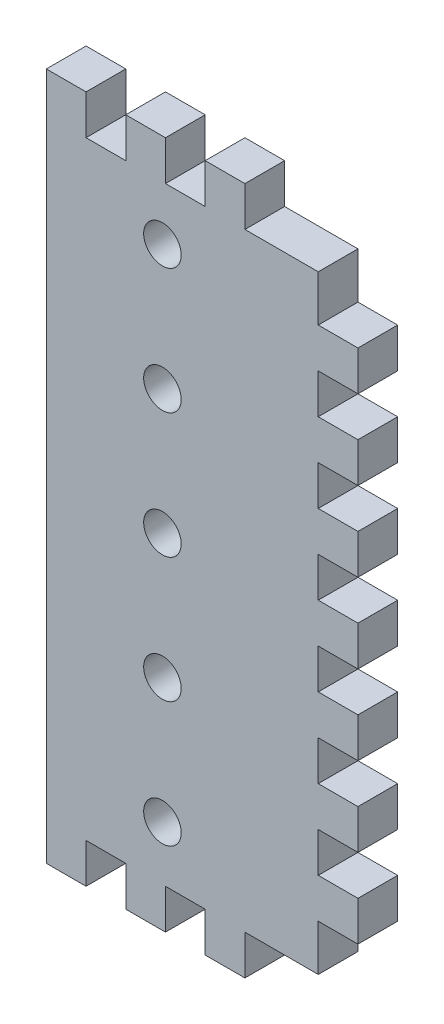
SolidWorks part; units mm, degrees
ref_plane "Front Plane" through (0, 0, 0) normal (0, 0, 1) x (1, 0, 0)
ref_plane "Top Plane" through (0, 0, 0) normal (0, 1, 0) x (1, 0, 0)
ref_plane "Right Plane" through (0, 0, 0) normal (1, 0, 0) x (0, 0, -1)
sketch "Sketch1" plane through (0, 0, 0) normal (0, 0, 1) x (1, 0, 0)
  line L1 (15.6312, -27.5) -> (-15.6312, -27.5)
  line L2 (15.6312, -27.5) -> (15.6312, 27.5)
  line L3 (15.6312, 27.5) -> (-15.6312, 27.5)
  line L4 (-15.6312, -27.5) -> (-15.6312, 27.5)
  line L5 (15.6312, -27.5) -> (-15.6312, 27.5) construction
  line L6 (15.6312, 27.5) -> (-15.6312, -27.5) construction
  point P0 (0, 0)
  dimension "D1" = 31.2625
  dimension "D2" = 55
extrude "Boss-Extrude1" add sketch "Sketch1" along normal blind 3.175
sketch "Sketch2" plane through (0, 0, 3.175) normal (0, 0, 1) x (1, 0, 0)
  line L0 (-15.6312, 27.5) -> (-15.6312, -27.5) construction
  circle A0 centre (0, 0) radius 1.5
  dimension "D1" = 3
extrude "Cut-Extrude1" cut sketch "Sketch2" against normal blind 10
pattern_linear "LPattern1" count 3 spacing 10 along (0, 1, 0) count 3 spacing 10 along (0, -1, 0) of "Cut-Extrude1"
sketch "Sketch3" plane through (0, 0, 3.175) normal (0, 0, 1) x (1, 0, 0)
  line L0 (15.6312, -27.5) -> (15.6312, 27.5) construction
  line L1 (12.4563, -1.5875) -> (18.8062, -1.5875)
  line L2 (12.4563, -1.5875) -> (12.4563, -4.7625)
  line L3 (12.4563, -4.7625) -> (18.8062, -4.7625)
  line L4 (18.8062, -1.5875) -> (18.8062, -4.7625)
  line L5 (12.4563, -1.5875) -> (18.8062, -4.7625) construction
  line L6 (12.4563, -4.7625) -> (18.8062, -1.5875) construction
  point P0 (15.6312, -3.175)
  dimension "D1" = 3.175
  dimension "D2" = 6.35
  dimension "D3" = 3.175
extrude "Cut-Extrude2" cut sketch "Sketch3" against normal blind 10
pattern_linear "LPattern2" count 5 spacing 6.35 along (0, 1, 0) count 5 spacing 6.35 along (0, -1, 0) of "Cut-Extrude2"
sketch "Sketch4" plane through (0, 0, 3.175) normal (0, 0, 1) x (1, 0, 0)
  line L1 (12.4563, 23.8125) -> (15.6312, 23.8125)
  line L2 (12.4563, 23.8125) -> (12.4563, 27.5)
  line L3 (12.4563, 27.5) -> (15.6312, 27.5)
  line L4 (15.6312, 23.8125) -> (15.6312, 27.5)
  line L5 (12.4563, -23.8125) -> (15.6312, -23.8125)
  line L6 (12.4563, -23.8125) -> (12.4563, -26.9875)
  line L7 (12.4563, -26.9875) -> (15.6312, -26.9875)
  line L8 (15.6312, -23.8125) -> (15.6312, -26.9875)
extrude "Cut-Extrude3" cut sketch "Sketch4" against normal blind 10
sketch "Sketch5" plane through (0, 0, 3.175) normal (0, 0, 1) x (1, 0, 0)
  line L0 (-15.6312, -27.5) -> (12.4563, -27.5) construction
  line L1 (-15.6312, 27.5) -> (-9.2812, 27.5)
  line L2 (-15.6312, 27.5) -> (-15.6312, -27.5)
  line L3 (-15.6312, -27.5) -> (-9.2812, -27.5)
  line L4 (-9.2812, 27.5) -> (-9.2812, -27.5)
  dimension "D1" = 6.35
extrude "Cut-Extrude4" cut sketch "Sketch5" against normal blind 10
sketch "Sketch6" plane through (0, 0, 3.175) normal (0, 0, 1) x (1, 0, 0)
  line L0 (12.4563, 27.5) -> (-9.2812, 27.5) construction
  line L1 (-6.1062, 27.5) -> (-2.9312, 27.5)
  line L2 (-6.1062, 27.5) -> (-6.1062, 24.325)
  line L3 (-6.1062, 24.325) -> (-2.9312, 24.325)
  line L4 (-2.9312, 27.5) -> (-2.9312, 24.325)
  line L5 (-9.2812, -27.5) -> (-9.2812, 27.5) construction
  dimension "D1" = 3.175
  dimension "D2" = 3.175
  dimension "D3" = 3.175
extrude "Cut-Extrude5" cut sketch "Sketch6" against normal blind 10
pattern_linear "LPattern3" count 2 spacing 6.35 along (1, 0, 0) count 2 spacing 6.35 of "Cut-Extrude5"
sketch "Sketch7" plane through (0, 0, 3.175) normal (0, 0, 1) x (1, 0, 0)
  line L0 (12.4563, 27.5) -> (12.4563, 20.6375) construction
  line L1 (6.5938, 27.5) -> (12.4563, 27.5)
  line L3 (6.5938, 24.325) -> (12.4563, 24.325)
  line L4 (12.4563, 27.5) -> (12.4563, 24.325)
  line L5 (6.5938, 27.5) -> (6.5938, 24.325)
extrude "Cut-Extrude6" cut sketch "Sketch7" against normal blind 10
mirror "Mirror1" about plane through (0, 0, 0) normal (0, 1, 0) of "LPattern3", "Cut-Extrude6", "Cut-Extrude5"
